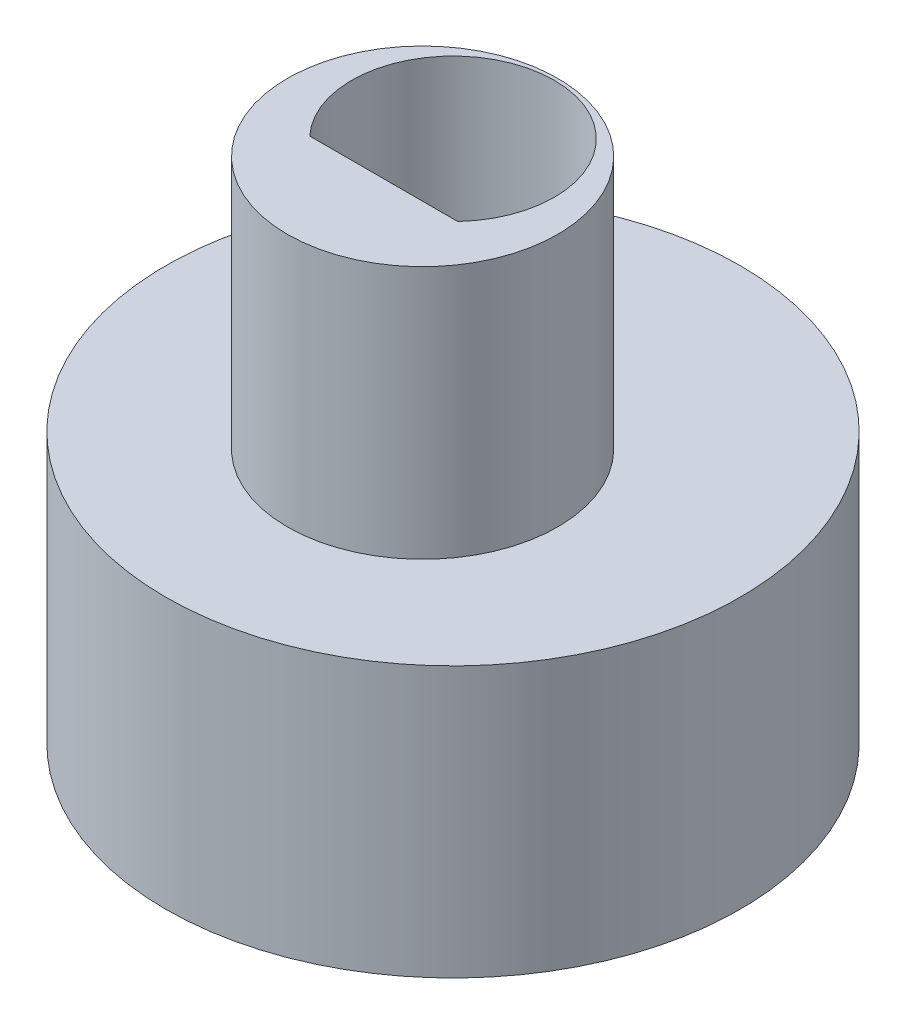
SolidWorks part; units mm, degrees
ref_plane "Front Plane" through (0, 0, 0) normal (0, 0, 1) x (1, 0, 0)
ref_plane "Top Plane" through (0, 0, 0) normal (0, 1, 0) x (1, 0, 0)
ref_plane "Right Plane" through (0, 0, 0) normal (1, 0, 0) x (0, 0, -1)
sketch "Sketch1" plane through (0, 0, 0) normal (0, 1, 0) x (1, 0, 0)
  circle A0 centre (0, 0) radius 4
  dimension "D1" = 8
extrude "Boss-Extrude1" add sketch "Sketch1" along normal blind 7.5
sketch "Sketch2" plane through (0, 0, 0) normal (0, -1, 0) x (-1, 0, 0)
  line L0 (2.1903, -1.15) -> (-2.1903, -1.15)
  circle A0 centre (0, 0.9) radius 3
  circle A1 centre (0, 0) radius 4 construction
  point P5 (0, 3.9)
  point P7 (0, 4)
  dimension "D1" = 6
  dimension "D2" = 2.05
  dimension "D3" = 0.1
extrude "Cut-Extrude2" cut sketch "Sketch2" against normal blind 10 contours L0 A0
sketch "Sketch4" plane through (0, 0, 0) normal (0, -1, 0) x (-1, 0, 0)
  line L0 (2.1903, -1.15) -> (-2.1903, -1.15)
  circle A0 centre (0, 0.9) radius 8.5
  arc A1 (2.1903, -1.15) -> (-2.1903, -1.15) centre (0, 0.9) ccw construction
  arc A2 (2.1903, -1.15) -> (-2.1903, -1.15) centre (0, 0.9) ccw
  dimension "D1" = 17
extrude "Boss-Extrude3" add sketch "Sketch4" along normal blind 8
